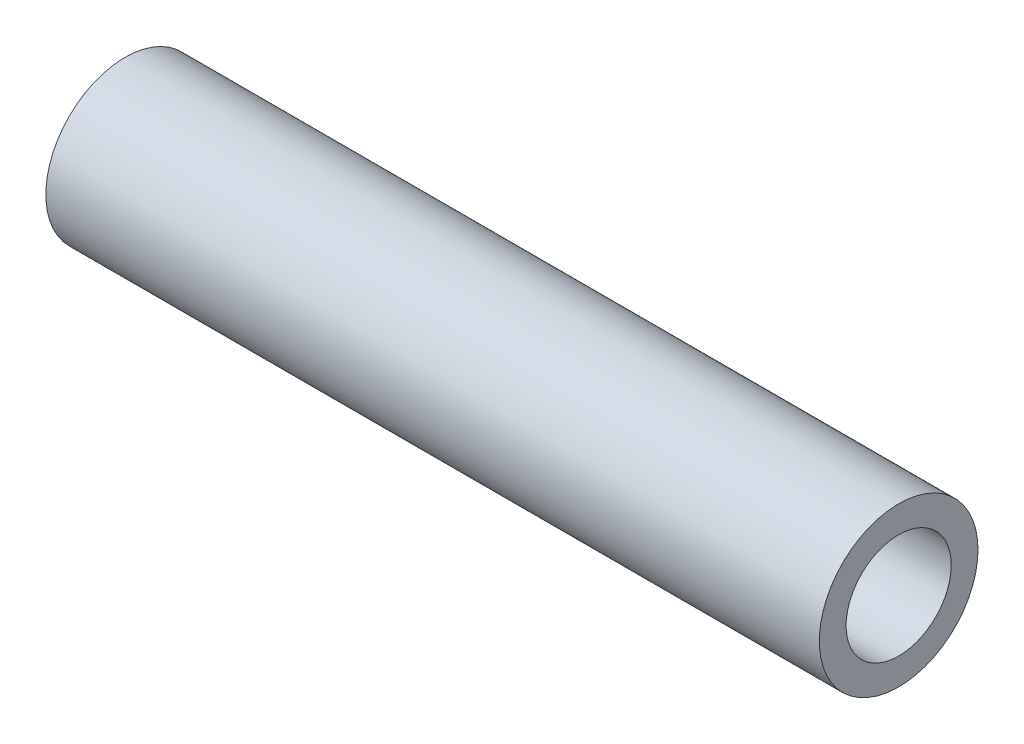
SolidWorks part; units mm, degrees
material "ABS"
ref_plane "前视基准面" through (0, 0, 0) normal (0, 0, 1) x (1, 0, 0)
ref_plane "上视基准面" through (0, 0, 0) normal (0, 1, 0) x (1, 0, 0)
ref_plane "右视基准面" through (0, 0, 0) normal (1, 0, 0) x (0, 0, -1)
other "Configuration Table"
sketch "草图1" plane through (0, 0, 0) normal (1, 0, 0) x (0, 0, -1)
  circle A0 centre (0, 0) radius 2.65
  circle A1 centre (0, 0) radius 4
  dimension "D1" = 5.3
  dimension "D2" = 8
extrude "凸台-拉伸1" add sketch "草图1" along normal blind 39
